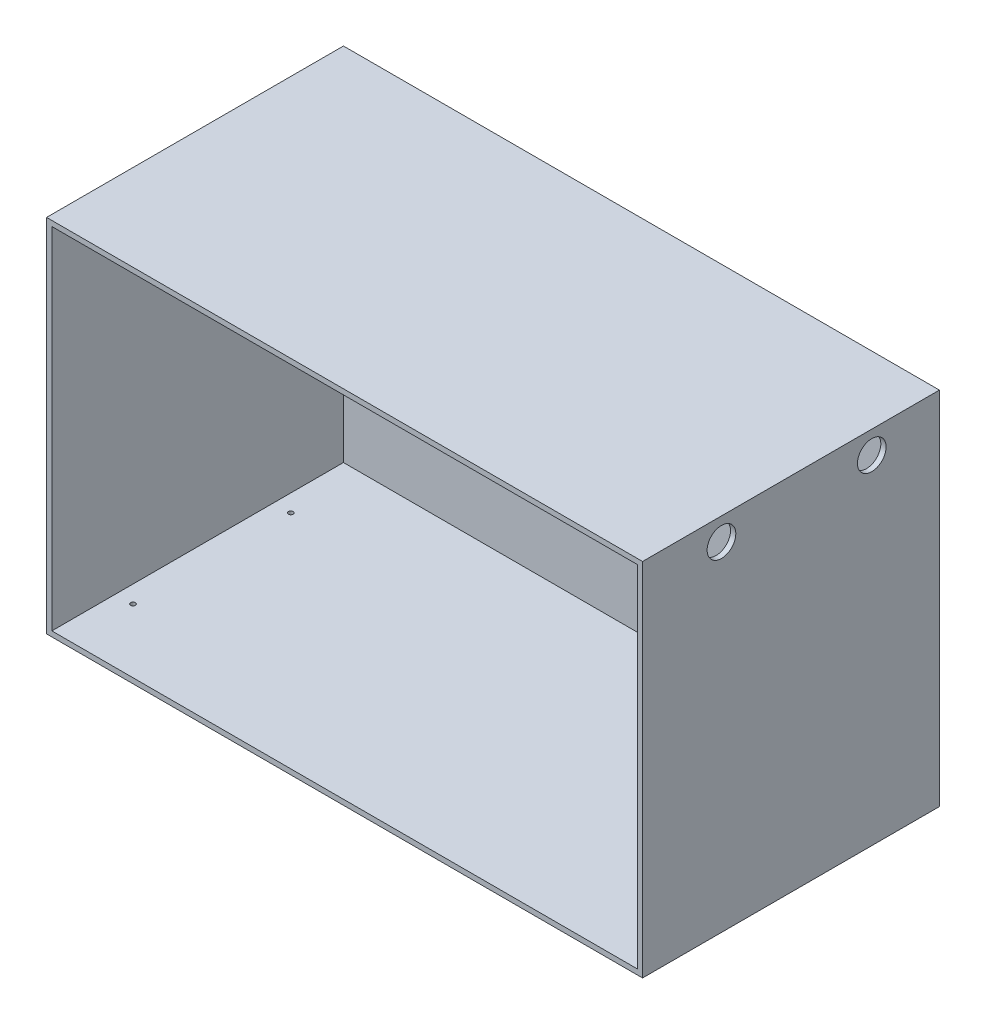
SolidWorks part; units mm, degrees
ref_plane "Alzado" through (0, 0, 0) normal (0, 0, 1) x (1, 0, 0)
ref_plane "Planta" through (0, 0, 0) normal (0, 1, 0) x (1, 0, 0)
ref_plane "Vista lateral" through (0, 0, 0) normal (1, 0, 0) x (0, 0, -1)
sketch "Croquis1" plane through (0, 0, 0) normal (0, 1, 0) x (1, 0, 0)
  line L1 (-396.5, 220) -> (396.5, 220)
  line L2 (-396.5, 220) -> (-396.5, -220)
  line L3 (-396.5, -220) -> (396.5, -220)
  line L4 (396.5, 220) -> (396.5, -220)
  line L5 (-396.5, 220) -> (396.5, -220) construction
  line L6 (-396.5, -220) -> (396.5, 220) construction
  point P0 (0, 0)
  dimension "D1" = 793
  dimension "D2" = 440
extrude "Saliente-Extruir1" add sketch "Croquis1" along normal blind 480
shell "Vaciado1" thickness 7
sketch "Croquis2" plane through (0, 0, 0) normal (0, -1, 0) x (1, 0, 0)
  line L0 (-327.9814, 41.2887) -> (-340.6814, 41.2887) construction
  line L1 (-346.5, 30) -> (-346.5, -220) construction
  line L2 (396.5, -220) -> (-396.5, -220) construction
  line L3 (-396.5, -220) -> (-396.5, 220) construction
  circle A0 centre (-340.6814, 41.2887) radius 12.7
  dimension "D1" = 25.4
  dimension "D2" = 250
  dimension "D3" = 50
extrude "Cortar-Extruir1" cut sketch "Croquis2" against normal blind 80
sketch "Croquis3" plane through (0, 0, 0) normal (0, -1, 0) x (1, 0, 0)
  line L0 (-340.6814, 41.2887) -> (-340.6814, 81.2887) construction
  circle A0 centre (-340.6814, 81.2887) radius 6.35
  dimension "D1" = 12.7
  dimension "D2" = 40
extrude "Cortar-Extruir2" cut sketch "Croquis3" against normal blind 10
sketch "Croquis5" plane through (0, 0, 0) normal (0, -1, 0) x (1, 0, 0)
  line L0 (-340.6814, 81.2887) -> (-340.6814, 121.2887) construction
  circle A0 centre (-340.6814, 121.2887) radius 6.35
  dimension "D2" = 12.7
  dimension "D1" = 40
extrude "Cortar-Extruir4" cut sketch "Croquis5" against normal blind 10
sketch "Croquis6" plane through (-396.5, 0, 0) normal (-1, 0, 0) x (0, 0, 1)
  line L0 (70, 450) -> (220, 450) construction
  line L1 (220, 480) -> (220, 0) construction
  line L2 (70, 450) -> (70, 480) construction
  line L3 (-220, 480) -> (220, 480) construction
  line L4 (70, 450) -> (-219.4947, 450) construction
  circle A0 centre (-130, 450) radius 19.05
  circle A1 centre (70, 450) radius 19.05
  dimension "D4" = 38.1
  dimension "D5" = 38.1
  dimension "D1" = 150
  dimension "D2" = 30
  dimension "D3" = 200
extrude "Cortar-Extruir5" cut sketch "Croquis6" against normal blind 848
sketch "Croquis7" plane through (0, 0, 0) normal (0, -1, 0) x (1, 0, 0)
  line L0 (0, 0) -> (0, 220) construction
  line L1 (-396.5, 220) -> (396.5, 220) construction
mirror "Simetría1" about plane through (0, 0, 0) normal (1, 0, 0) of "Cortar-Extruir1", "Cortar-Extruir2", "Cortar-Extruir4"
sketch "Croquis8" plane through (0, 0, 0) normal (0, -1, 0) x (1, 0, 0)
  line L0 (340.6814, 28.5887) -> (340.6814, -121.4113) construction
  circle A0 centre (340.6814, 41.2887) radius 12.7 construction
  circle A1 centre (340.6814, -121.4113) radius 12.7
  dimension "D1" = 25.4
  dimension "D2" = 150
extrude "Cortar-Extruir6" cut sketch "Croquis8" against normal blind 10
sketch "Croquis9" plane through (0, 7, 0) normal (0, 1, 0) x (1, 0, 0)
  line L1 (-358.2076, 41.3987) -> (-323.1553, 41.3987)
  line L2 (-358.2076, 41.3987) -> (-358.2076, -203.976)
  line L3 (-358.2076, -203.976) -> (-323.1553, -203.976)
  line L4 (-323.1553, 41.3987) -> (-323.1553, -203.976)
  line L5 (-358.2076, 41.3987) -> (-323.1553, -203.976) construction
  line L6 (-358.2076, -203.976) -> (-323.1553, 41.3987) construction
  point P0 (-340.6814, -81.2887)
extrude "Saliente-Extruir2" add sketch "Croquis9" against normal blind 7
sketch "Croquis10" plane through (0, 0, 0) normal (0, -1, 0) x (-1, 0, 0)
  line L0 (275, 175) -> (396.5, 175) construction
  line L1 (396.5, 220) -> (396.5, -220) construction
  line L2 (275, 175) -> (275, 220) construction
  line L3 (-396.5, 220) -> (396.5, 220) construction
  circle A0 centre (-275, 175) radius 3.97
  circle A1 centre (-275, -81.2) radius 3.97
  circle A2 centre (275, 175) radius 3.9688
  circle A3 centre (275, -81.2) radius 3.97
  dimension "D1" = 7.94
  dimension "D2" = 7.94
  dimension "D3" = 7.94
sketch "Croquis12" plane through (0, 0, -213) normal (0, 0, 1) x (1, 0, 0)
  line L0 (0, 7) -> (0, 473) construction
  line L1 (-389.5, 7) -> (389.5, 7) construction
  line L2 (389.5, 473) -> (-389.5, 473) construction
  line L3 (0, 240) -> (24.0252, 240) construction
  line L4 (-389.5, 473) -> (389.5, 473) construction
  line L5 (-369.5, 27) -> (369.5, 27)
  line L6 (-369.5, 27) -> (-369.5, 453)
  line L7 (-369.5, 453) -> (369.5, 453)
  line L8 (369.5, 27) -> (369.5, 453)
  line L9 (-369.5, 27) -> (369.5, 453) construction
  line L10 (-369.5, 453) -> (369.5, 27) construction
  line L11 (389.5, 473) -> (389.5, 7) construction
  dimension "D1" = 20
  dimension "D2" = 20
sketch "Croquis13" plane through (389.5, 0, 0) normal (-1, 0, 0) x (0, 0, 1)
  line L0 (3.5, 7) -> (3.5, 473) construction
  line L1 (220, 7) -> (-213, 7) construction
  line L2 (220, 473) -> (-213, 473) construction
  line L3 (3.5, 473) -> (3.5, 240) construction
  line L4 (3.5, 240) -> (45.2661, 240) construction
  line L5 (220, 473) -> (220, 7) construction
  line L6 (-193, 453) -> (200, 453)
  line L7 (-193, 453) -> (-193, 27)
  line L8 (-193, 27) -> (200, 27)
  line L9 (200, 453) -> (200, 27)
  line L10 (-193, 453) -> (200, 27) construction
  line L11 (-193, 27) -> (200, 453) construction
  dimension "D1" = 20
  dimension "D2" = 20
sketch "Croquis14" plane through (-396.5, 0, 0) normal (-1, 0, 0) x (0, 0, 1)
  line L0 (-183, 480) -> (-183, 393) construction
  line L1 (-193, 27) -> (200, 27)
  line L2 (-193, 27) -> (-193, 453)
  line L3 (-193, 453) -> (200, 453)
  line L4 (200, 27) -> (200, 453)
  line L5 (-193, 27) -> (200, 453) construction
  line L6 (-193, 453) -> (200, 27) construction
  line L7 (-220, 480) -> (220, 480) construction
  line L8 (-183, 393) -> (-220, 393) construction
  line L9 (-220, 480) -> (-220, 0) construction
  line L10 (-193, 453) -> (-193, 403)
  line L11 (-193, 403) -> (200, 403)
  line L12 (3.5, 240) -> (45.2661, 240) construction
  line L13 (3.5, 240) -> (3.5, 173.2105) construction
  line L14 (3.5, 7) -> (3.5, 473) construction
  circle A0 centre (-183, 393) radius 3.175
  circle A1 centre (190, 393) radius 3.175
  circle A2 centre (-183, 37) radius 3.175 construction
  circle A3 centre (190, 37) radius 3.175 construction
  circle A4 centre (-193, 27) radius 3.175
  circle A5 centre (200, 27) radius 3.175
  point P0 (3.5, 240)
  dimension "D4" = 6.35
  dimension "D5" = 10
  dimension "D6" = 10
  dimension "D7" = 6.35
  dimension "D8" = 6.35
  dimension "D9" = 6.35
  dimension "D1" = 10
  dimension "D2" = 10
  dimension "D3" = 50
sketch "Croquis15" plane through (0, 0, 0) normal (0, -1, 0) x (1, 0, 0)
  line L0 (-366.5, -120) -> (-366.5, -220) construction
  line L1 (-366.5, -120) -> (-396.5, -120) construction
  line L2 (-396.5, -220) -> (-396.5, 220) construction
  line L3 (0, 0) -> (0, -220) construction
  line L4 (396.5, -220) -> (-396.5, -220) construction
  line L5 (0, 0) -> (14.2284, 0) construction
  line L6 (0, -15) -> (113.2183, -15) construction
  line L7 (-366.5, 220) -> (-366.5, 90) construction
  line L8 (-396.5, 220) -> (396.5, 220) construction
  circle A0 centre (-366.5, -120) radius 3.175
  circle A1 centre (-366.5, 90) radius 3.175
  circle A2 centre (366.5, -120) radius 3.175
  circle A3 centre (366.5, 90) radius 3.175
  dimension "D3" = 6.35
  dimension "D1" = 30
  dimension "D2" = 100
  dimension "D4" = 130
extrude "Cortar-Extruir10" cut sketch "Croquis15" against normal blind 10
sketch "Croquis16" plane through (-396.5, 0, 0) normal (-1, 0, 0) x (0, 0, 1)
  line L0 (220, 480) -> (220, 0) construction
  line L1 (-225, 401.7269) -> (220, 401.7269)
  line L2 (-225, 401.7269) -> (-225, 0)
  line L3 (-225, 0) -> (220, 0)
  line L4 (220, 401.7269) -> (220, 0)
  line L5 (-225, 401.7269) -> (220, 0) construction
  line L6 (-225, 0) -> (220, 401.7269) construction
  point P0 (-2.5, 200.8635)
sketch "Croquis18" plane through (0, 0, -213) normal (0, 0, 1) x (1, 0, 0)
  line L0 (-348.7422, 441.087) -> (-348, 438) construction
  line L1 (-348, 438) -> (-344.913, 438.7422) construction
  circle A0 centre (-348, 438) radius 3.175
  circle A1 centre (0, 438) radius 3.175
  circle A2 centre (348, 438) radius 3.175
  circle A3 centre (348, 240) radius 3.175
  circle A4 centre (348, 42) radius 3.175
  circle A5 centre (0, 42) radius 3.175
  circle A6 centre (-348, 42) radius 3.175
  circle A7 centre (-348, 240) radius 5.5549
extrude "Cortar-Extruir12" cut sketch "Croquis18" against normal blind 10
sketch "Croquis19" plane through (0, 0, 220) normal (0, 0, 1) x (1, 0, 0)
  line L0 (-389.5, 240) -> (0, 240) construction
  line L1 (-389.5, 473) -> (-389.5, 7) construction
  line L2 (0, 240) -> (0, 0) construction
  line L4 (-396.5, 0) -> (396.5, 0)
  line L5 (-396.5, 0) -> (-396.5, 480)
  line L6 (-396.5, 480) -> (396.5, 480)
  line L7 (396.5, 0) -> (396.5, 480)
  line L8 (-396.5, 0) -> (396.5, 480) construction
  line L9 (-396.5, 480) -> (396.5, 0) construction
extrude "Cortar-Extruir13" cut sketch "Croquis19" against normal blind 45
sketch "Croquis20" plane through (0, 0, 0) normal (0, -1, 0) x (1, 0, 0)
  line L1 (316.4197, 137.6096) -> (356.6426, 137.6096)
  line L2 (316.4197, 137.6096) -> (316.4197, -197.5808)
  line L3 (316.4197, -197.5808) -> (356.6426, -197.5808)
  line L4 (356.6426, 137.6096) -> (356.6426, -197.5808)
  line L5 (316.4197, 137.6096) -> (356.6426, -197.5808) construction
  line L6 (316.4197, -197.5808) -> (356.6426, 137.6096) construction
  point P0 (336.5311, -29.9856)
extrude "Saliente-Extruir3" add sketch "Croquis20" against normal blind 7
sketch "Croquis21" plane through (0, 0, 0) normal (0, -1, 0) x (1, 0, 0)
  line L0 (396.5, -220) -> (316.5, -220) construction
  line L1 (396.5, -220) -> (-396.5, -220) construction
  line L2 (316.5, -220) -> (316.5, 175) construction
  line L3 (-396.5, 175) -> (396.5, 175) construction
  circle A0 centre (316.5, -144.9784) radius 12.7
  dimension "D2" = 25.4
  dimension "D1" = 80
sketch "Croquis22" plane through (0, 0, -220) normal (0, 0, -1) x (-1, 0, 0)
  line L1 (-375.2804, 466.7691) -> (379.4355, 466.7691)
  line L2 (-375.2804, 466.7691) -> (-375.2804, 19.4447)
  line L3 (-375.2804, 19.4447) -> (379.4355, 19.4447)
  line L4 (379.4355, 466.7691) -> (379.4355, 19.4447)
  line L5 (-375.2804, 466.7691) -> (379.4355, 19.4447) construction
  line L6 (-375.2804, 19.4447) -> (379.4355, 466.7691) construction
  point P0 (2.0775, 243.1069)
extrude "Saliente-Extruir4" add sketch "Croquis22" against normal blind 7
